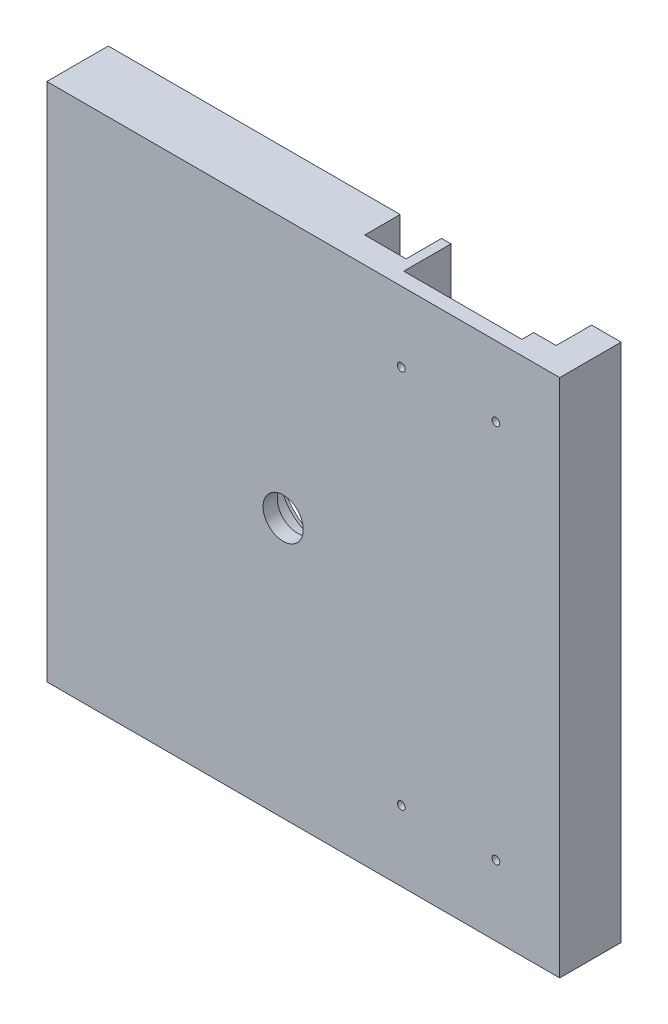
SolidWorks part; units mm, degrees
ref_plane "Plano frontal" through (0, 0, 0) normal (0, 0, 1) x (1, 0, 0)
ref_plane "Plano superior" through (0, 0, 0) normal (0, 1, 0) x (1, 0, 0)
ref_plane "Plano direito" through (0, 0, 0) normal (1, 0, 0) x (0, 0, -1)
sketch "Esboço1" plane through (15, 0, 10.5) normal (0, 0, 1) x (1, 0, 0)
  line L6 (102, -110) -> (-115, -110)
  line L7 (102, -110) -> (102, 110)
  line L8 (102, 110) -> (-115, 110)
  line L9 (-115, -110) -> (-115, 110)
  dimension "D1" = 110
  dimension "D2" = 110
  dimension "D3" = 100
  dimension "D4" = 117
extrude "Ressalto-extrusão1" add sketch "Esboço1" along normal blind 26
sketch "Esboço2" plane through (0, 0, 10.5) normal (0, 0, -1) x (-1, 0, 0)
  circle A0 centre (0, 0) radius 30
extrude "Corte-extrusão3" cut sketch "Esboço2" against normal up to vertex (10 mm away) contours A0
sketch "Esboço4" plane through (0, 0, 10.5) normal (0, 0, -1) x (-1, 0, 0)
  line L0 (-41, -110) -> (-41, 110)
  line L1 (-41, 72.4) -> (-41, -72.4) construction
  line L2 (-23.5, -110) -> (-23.5, 110)
  line L3 (-24, 71.4023) -> (-24, 73.1074) construction
  line L4 (100, -110) -> (-117, -110) construction
  line L5 (-117, 110) -> (100, 110) construction
  line L6 (-23.5, -110) -> (-41, -110)
  line L7 (-41, 110) -> (-23.5, 110)
  dimension "D1" = 0.5
extrude "Corte-extrusão4" cut sketch "Esboço4" against normal up to vertex (15 mm away)
sketch "Esboço5" plane through (0, 0, 10.5) normal (0, 0, -1) x (-1, 0, 0)
  line L0 (-41, 72.4) -> (-41, -72.4) construction
  line L2 (-41, -52.3) -> (-41, 52.3)
  line L5 (-45, -52.3) -> (-45, -138.0623)
  line L6 (-41, -52.3) -> (-45, -52.3)
  line L7 (-45, 52.3) -> (-41, 52.3)
  line L8 (-45, 52.3) -> (-45, 121.6712)
  line L17 (-104.5, 121.6712) -> (-45, 121.6712)
  line L19 (-45, -138.0623) -> (-104.5, -138.0623)
  line L20 (-104.5, -138.0623) -> (-104.5, 121.6712)
  dimension "D3" = 63.5
extrude "Corte-extrusão5" cut sketch "Esboço5" against normal up to surface (15 mm away) up to face at (32.25, 0, 25.5)
sketch "Esboço8" plane through (0, 0, 20.5) normal (0, 0, -1) x (-1, 0, 0)
  circle A0 centre (0, 0) radius 17.5
  circle A1 centre (0, 0) radius 17.5 construction
extrude "Corte-extrusão8" cut sketch "Esboço8" against normal blind 10
sketch "Esboço9" plane through (0, 0, 30.5) normal (0, 0, -1) x (-1, 0, 0)
  circle A0 centre (0, 0) radius 8.5
  dimension "D1" = 17
extrude "Corte-extrusão9" cut sketch "Esboço9" against normal through all contours A0
sketch "Esboço10" plane through (0, 0, 25.5) normal (0, 0, -1) x (-1, 0, 0)
  line L0 (-45, -110) -> (-45, -52.3) construction
  line L1 (-95, -52.3) -> (-45, -52.3)
  line L2 (-95, -52.3) -> (-95, -129.2145)
  line L3 (-95, -129.2145) -> (-45, -129.2145)
  line L4 (-45, -52.3) -> (-45, -129.2145)
  line L5 (-45, 52.3) -> (-95, 52.3)
  line L6 (-45, 52.3) -> (-45, 126.4135)
  line L7 (-45, 126.4135) -> (-95, 126.4135)
  line L8 (-95, 52.3) -> (-95, 126.4135)
extrude "Corte-extrusão10" cut sketch "Esboço10" against normal up to vertex (5 mm away)
fillet "Filete1" radius 3 4 edges at (95, 52.3, 28) (45, 52.3, 28) (95, -52.3, 28) (45, -52.3, 28)
hole_wizard "Furo roscado de M6x1.01" positions "Esboço11" profile "Esboço12" tap size "M6x1.0" standard "Ansi Metric"
sketch "Esboço11" plane through (0, 0, 10.5) normal (0, 0, -1) x (-1, 0, 0)
  line L0 (-117, -110) -> (-117, 110) construction
  line L1 (100, 110) -> (100, -110) construction
  point P0 (-110.5, -100)
  point P2 (-110.5, 0)
  point P4 (-110.5, 100)
  point P6 (93.5, 100)
  point P8 (93.5, 0)
  point P10 (93.5, -100)
  dimension "D1" = 6.5
  dimension "D2" = 100
  dimension "D3" = 100
  dimension "D4" = 6.5
sketch "Esboço12" plane through (110.5, -100, 10.5) normal (1, 0, 0) x (0, 1, 0)
  line L0 (0, 0) -> (0, 18.5022)
  line L1 (0, 18.5022) -> (2.5, 17)
  line L2 (2.5, 17) -> (2.5, 0.525)
  line L3 (2.5, 0.525) -> (3.025, 0)
  line L5 (3.025, 0) -> (0, 0)
  line L6 (-2.5, 0.525) -> (-3.025, 0) construction
  line L10 (0, 18.5022) -> (-2.5, 17) construction
  line L11 (0, -6.35) -> (0, 107.95) construction
  dimension "Tap Drill Dia." = 5
  dimension "Tap Drill Depth" = 17
  dimension "Near C'Sink Dia." = 6.05
  dimension "Near C'Sink Angle" = 90
  dimension "Drill Angle" = 118
cosmetic thread "Rosca de furo1" parameters "D1"=12, "D2"=6
cosmetic thread "Rosca de furo2" parameters "D1"=12, "D2"=6
cosmetic thread "Rosca de furo3" parameters "D1"=12, "D2"=6
cosmetic thread "Rosca de furo4" parameters "D1"=12, "D2"=6
cosmetic thread "Rosca de furo5" parameters "D1"=12, "D2"=6
cosmetic thread "Rosca de furo6" parameters "D1"=12, "D2"=6
hole_wizard "Furo roscado de M4x0.71" positions "Esboço13" profile "Esboço14" tap size "M4x0.7" standard "Ansi Metric"
sketch "Esboço13" plane through (0, 0, 30.5) normal (0, 0, -1) x (-1, 0, 0)
  point P0 (-90, -80.3)
  point P3 (-50, -80.3)
  point P6 (-90, 80.3)
  point P9 (-50, 80.3)
sketch "Esboço14" plane through (90, -80.3, 30.5) normal (1, 0, 0) x (0, 1, 0)
  line L0 (0, 0) -> (0, 12.4914)
  line L1 (0, 12.4914) -> (1.65, 11.5)
  line L2 (1.65, 11.5) -> (1.65, 0.375)
  line L3 (1.65, 0.375) -> (2.025, 0)
  line L5 (2.025, 0) -> (0, 0)
  line L6 (-1.65, 0.375) -> (-2.025, 0) construction
  line L10 (0, 12.4914) -> (-1.65, 11.5) construction
  line L11 (0, -6.35) -> (0, 107.95) construction
  dimension "Tap Drill Dia." = 3.3
  dimension "Tap Drill Depth" = 11.5
  dimension "Near C'Sink Dia." = 4.05
  dimension "Near C'Sink Angle" = 90
  dimension "Drill Angle" = 118
cosmetic thread "Rosca de furo7" parameters "D1"=8, "D2"=4
cosmetic thread "Rosca de furo8" parameters "D1"=8, "D2"=4
cosmetic thread "Rosca de furo9" parameters "D1"=8, "D2"=4
cosmetic thread "Rosca de furo10" parameters "D1"=8, "D2"=4
